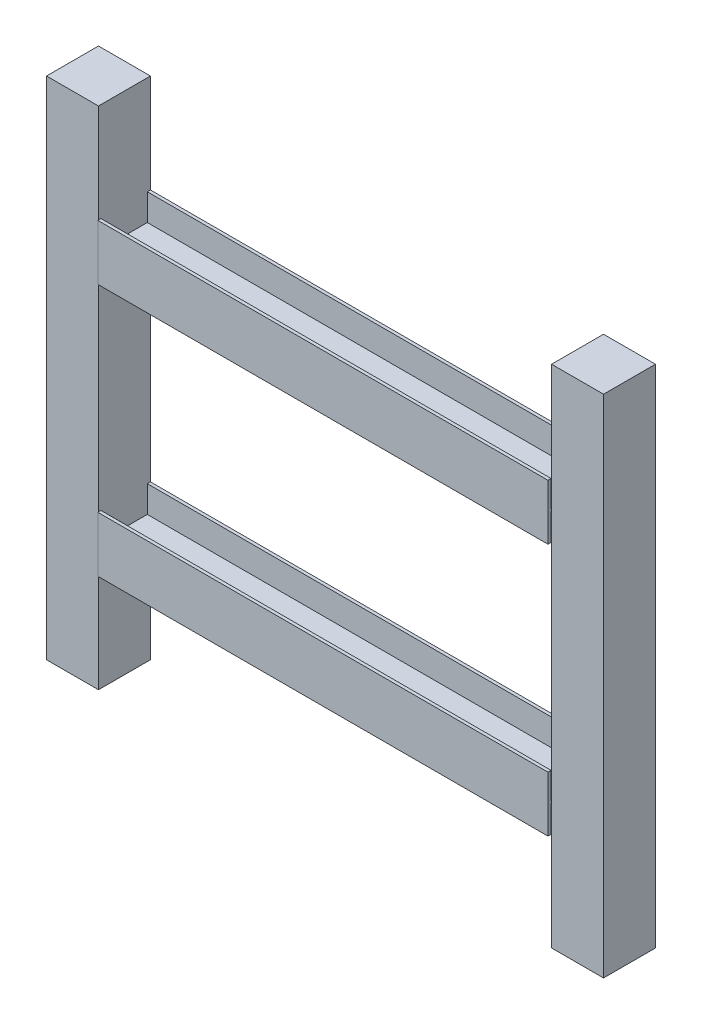
SolidWorks part; units mm, degrees
ref_plane "Front Plane" through (0, 0, 0) normal (0, 0, 1) x (1, 0, 0)
ref_plane "Top Plane" through (0, 0, 0) normal (0, 1, 0) x (1, 0, 0)
ref_plane "Right Plane" through (0, 0, 0) normal (1, 0, 0) x (0, 0, -1)
sketch "Sketch1" plane through (0, 0, 0) normal (0, 1, 0) x (1, 0, 0)
  line L0 (1409.4623, -27.9895) -> (1559.4623, -27.9895)
  line L1 (-40.5377, -36.4342) -> (109.4623, -36.4342)
  line L2 (-40.5377, -36.4342) -> (-40.5377, 113.5658)
  line L3 (-40.5377, 113.5658) -> (109.4623, 113.5658)
  line L4 (109.4623, -36.4342) -> (109.4623, 113.5658)
  line L5 (1409.4623, -27.9895) -> (1409.4623, 122.0105)
  line L6 (1409.4623, 122.0105) -> (1559.4623, 122.0105)
  line L7 (1559.4623, -27.9895) -> (1559.4623, 122.0105)
  dimension "D1" = 1300
extrude "Boss-Extrude1" add sketch "Sketch1" along normal blind 1460
sketch "Sketch3" plane through (109.4623, 0, 0) normal (1, 0, 0) x (0, 0, -1)
  line L0 (-38.4342, 285) -> (-38.4342, 445)
  line L1 (113.5658, 445) -> (113.5658, 285)
  line L2 (-38.4342, 285) -> (-29.4342, 285)
  line L3 (-38.4342, 445) -> (-29.4342, 445)
  line L4 (113.5658, 285) -> (104.5658, 285)
  line L5 (113.5658, 445) -> (104.5658, 445)
  line L6 (-29.4342, 285) -> (-29.4342, 362)
  line L7 (-29.4342, 1098) -> (-29.4342, 1175)
  line L8 (-29.4342, 362) -> (104.5658, 362)
  line L9 (104.5658, 1092) -> (104.5658, 1015)
  line L10 (-29.4342, 368) -> (104.5658, 368)
  line L11 (104.5658, 445) -> (104.5658, 368)
  line L12 (113.5658, 1460) -> (113.5658, 0) construction
  line L13 (113.5658, 0) -> (113.5658, 365) construction
  line L14 (113.5658, 365) -> (113.5658, 1095) construction
  line L15 (-38.4342, 1015) -> (-38.4342, 1175)
  line L16 (113.5658, 1175) -> (113.5658, 1015)
  line L17 (-38.4342, 1015) -> (-29.4342, 1015)
  line L18 (-38.4342, 1175) -> (-29.4342, 1175)
  line L19 (113.5658, 1015) -> (104.5658, 1015)
  line L20 (113.5658, 1175) -> (104.5658, 1175)
  line L21 (-29.4342, 1015) -> (-29.4342, 1092)
  line L22 (104.5658, 362) -> (104.5658, 285)
  line L23 (-29.4342, 1092) -> (104.5658, 1092)
  line L24 (-29.4342, 368) -> (-29.4342, 445)
  line L25 (-29.4342, 1098) -> (104.5658, 1098)
  line L26 (104.5658, 1175) -> (104.5658, 1098)
extrude "Boss-Extrude2" add sketch "Sketch3" along normal blind 1300 separate body
